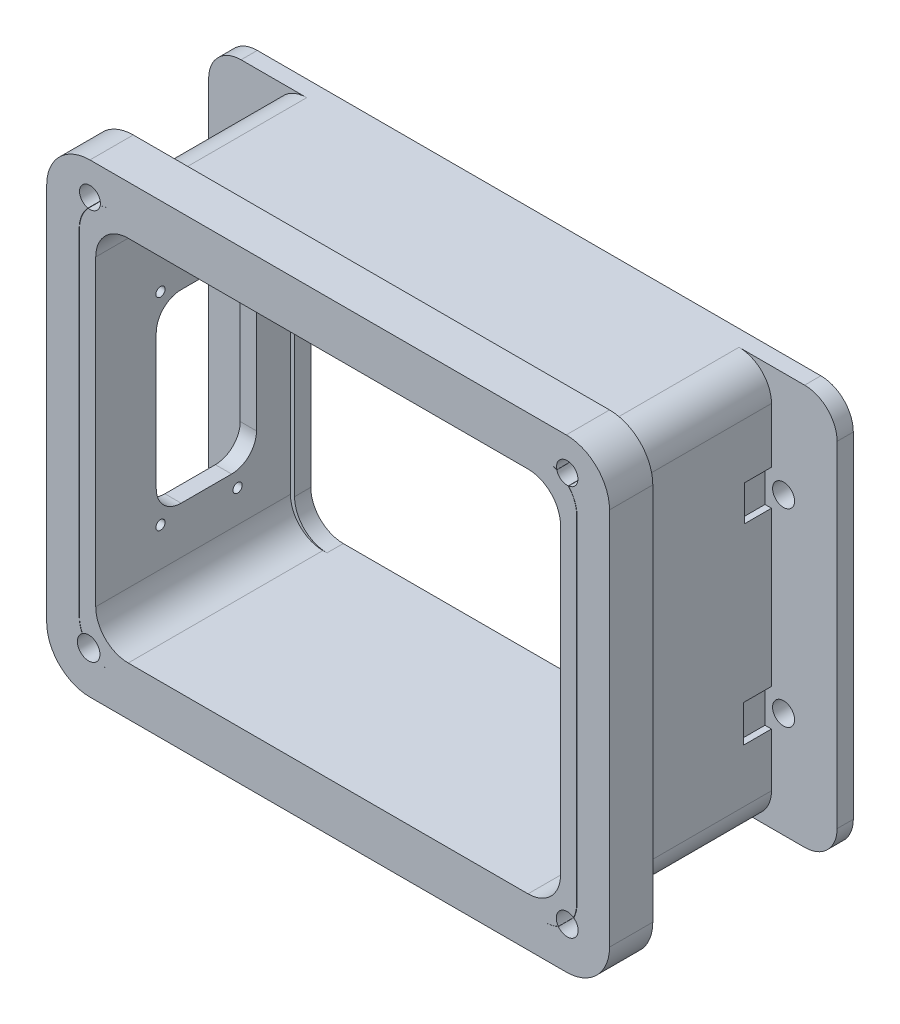
SolidWorks part; units mm, degrees
ref_plane "Front Plane" through (0, 0, 0) normal (0, 0, 1) x (1, 0, 0)
ref_plane "Top Plane" through (0, 0, 0) normal (0, 1, 0) x (1, 0, 0)
ref_plane "Right Plane" through (0, 0, 0) normal (1, 0, 0) x (0, 0, -1)
sketch "Sketch1" plane through (0, 0, 0) normal (0, 0, 1) x (1, 0, 0)
  line L0 (66.1502, -46.99) -> (-66.1502, -46.99)
  line L1 (73.7702, -39.37) -> (73.7702, 39.37)
  line L2 (66.1502, 46.99) -> (-66.1502, 46.99)
  line L3 (-73.7702, -39.37) -> (-73.7702, 39.37)
  line L4 (73.7702, -46.99) -> (-73.7702, 46.99) construction
  line L5 (73.7702, 46.99) -> (-73.7702, -46.99) construction
  line L6 (45.9749, -43.18) -> (-45.9749, -43.18)
  line L7 (53.5949, -35.56) -> (53.5949, 35.56)
  line L8 (45.9749, 43.18) -> (-45.9749, 43.18)
  line L9 (-53.5949, -35.56) -> (-53.5949, 35.56)
  line L10 (53.5949, -43.18) -> (-53.5949, 43.18) construction
  line L11 (53.5949, 43.18) -> (-53.5949, -43.18) construction
  arc A0 (-66.1502, 46.99) -> (-73.7702, 39.37) centre (-66.1502, 39.37) ccw
  arc A1 (73.7702, 39.37) -> (66.1502, 46.99) centre (66.1502, 39.37) ccw
  arc A2 (66.1502, -46.99) -> (73.7702, -39.37) centre (66.1502, -39.37) ccw
  arc A3 (-66.1502, -46.99) -> (-73.7702, -39.37) centre (-66.1502, -39.37) cw
  arc A4 (-45.9749, 43.18) -> (-53.5949, 35.56) centre (-45.9749, 35.56) ccw
  arc A5 (-45.9749, -43.18) -> (-53.5949, -35.56) centre (-45.9749, -35.56) cw
  arc A6 (45.9749, -43.18) -> (53.5949, -35.56) centre (45.9749, -35.56) ccw
  arc A7 (53.5949, 35.56) -> (45.9749, 43.18) centre (45.9749, 35.56) ccw
  point P0 (0, 0)
  point P5 (0, 0)
  dimension "D1" = 7.62
  dimension "D2" = 7.62
  dimension "D3" = 7.62
  dimension "D4" = 7.62
  dimension "D5" = 7.62
  dimension "D6" = 7.62
  dimension "D7" = 7.62
  dimension "D8" = 7.62
  dimension "D9" = 3.81
  dimension "D10" = 93.98
extrude "Boss-Extrude1" add sketch "Sketch1" along normal blind 3.81
sketch "Sketch2" plane through (0, 0, 3.81) normal (0, 0, 1) x (1, 0, 0)
  line L0 (66.1502, 46.99) -> (-66.1502, 46.99) construction
  line L1 (46.9359, -43.18) -> (-46.9359, -43.18)
  line L2 (54.5559, -35.56) -> (54.5559, 35.56)
  line L3 (46.9359, 43.18) -> (-46.9359, 43.18)
  line L4 (-54.5559, -35.56) -> (-54.5559, 35.56)
  line L5 (54.5559, -43.18) -> (-54.5559, 43.18) construction
  line L6 (54.5559, 43.18) -> (-54.5559, -43.18) construction
  line L7 (50.7459, -46.99) -> (-50.7459, -46.99)
  line L8 (58.3659, -39.37) -> (58.3659, 39.37)
  line L9 (50.7459, 46.99) -> (-50.7459, 46.99)
  line L10 (-58.3659, -39.37) -> (-58.3659, 39.37)
  line L11 (58.3659, -46.99) -> (-58.3659, 46.99) construction
  line L12 (58.3659, 46.99) -> (-58.3659, -46.99) construction
  arc A0 (-46.9359, 43.18) -> (-54.5559, 35.56) centre (-46.9359, 35.56) ccw
  arc A1 (54.5559, 35.56) -> (46.9359, 43.18) centre (46.9359, 35.56) ccw
  arc A2 (46.9359, -43.18) -> (54.5559, -35.56) centre (46.9359, -35.56) ccw
  arc A3 (-46.9359, -43.18) -> (-54.5559, -35.56) centre (-46.9359, -35.56) cw
  arc A4 (-50.7459, 46.99) -> (-58.3659, 39.37) centre (-50.7459, 39.37) ccw
  arc A5 (58.3659, 39.37) -> (50.7459, 46.99) centre (50.7459, 39.37) ccw
  arc A6 (50.7459, -46.99) -> (58.3659, -39.37) centre (50.7459, -39.37) ccw
  arc A7 (-50.7459, -46.99) -> (-58.3659, -39.37) centre (-50.7459, -39.37) cw
  point P0 (0, 0)
  point P18 (0, 0)
  dimension "D3" = 7.62
  dimension "D4" = 7.62
  dimension "D5" = 7.62
  dimension "D6" = 7.62
  dimension "D9" = 7.62
  dimension "D10" = 7.62
  dimension "D11" = 7.62
  dimension "D12" = 7.62
  dimension "D2" = 3.81
  dimension "D7" = 3.81
  dimension "D8" = 116.7317
extrude "Boss-Extrude2" add sketch "Sketch2" along normal blind 45.72
sketch "Sketch4" plane through (0, 0, 3.81) normal (0, 0, 1) x (1, 0, 0)
  circle A0 centre (61.206, 22.2292) radius 2.58
  circle A1 centre (61.206, -22.2208) radius 2.58
  circle A2 centre (-60.974, -22.2208) radius 2.58
  circle A3 centre (-60.974, 22.2292) radius 2.58
extrude "Cut-Extrude1" cut sketch "Sketch4" against normal up to next
sketch "Sketch7" plane through (-58.3659, 0, 0) normal (-1, 0, 0) x (0, 0, 1)
  line L0 (11.7913, 13.0336) -> (11.7913, -18.6824)
  line L1 (17.6333, 18.8756) -> (29.482, 18.8756)
  line L2 (35.324, 13.0336) -> (35.324, -18.6824)
  line L3 (17.6333, -24.5244) -> (29.482, -24.5244)
  arc A0 (11.7913, 13.0336) -> (17.6333, 18.8756) centre (17.6333, 13.0336) cw
  arc A1 (29.482, 18.8756) -> (35.324, 13.0336) centre (29.482, 13.0336) cw
  arc A2 (35.324, -18.6824) -> (29.482, -24.5244) centre (29.482, -18.6824) cw
  arc A3 (11.7913, -18.6824) -> (17.6333, -24.5244) centre (17.6333, -18.6824) ccw
  dimension "D1" = 5.842
  dimension "D2" = 5.842
  dimension "D3" = 5.842
  dimension "D4" = 5.842
extrude "Cut-Extrude2" cut sketch "Sketch7" against normal up to next
sketch "Sketch8" plane through (-54.5559, 0, 0) normal (1, 0, 0) x (0, 0, -1)
  circle A0 centre (-34.324, -26.5244) radius 1.085
  circle A1 centre (-16.224, -28.0244) radius 1.085
  circle A2 centre (-16.224, 22.3756) radius 1.085
  circle A3 centre (-34.324, 20.8756) radius 1.085
extrude "Cut-Extrude3" cut sketch "Sketch8" against normal up to next
ref_plane "Plane2" through (53.5949, 35.56, 0) normal (0, 1, 0) x (1, 0, 0)
sketch "Sketch10" plane through (-58.3659, 0, 0) normal (-1, 0, 0) x (0, 0, 1)
  line L0 (3.81, 39.37) -> (3.81, -39.37) construction
  line L1 (3.81, 26.4109) -> (10.0914, 26.4109)
  line L2 (3.81, 26.4109) -> (3.81, 18.0723)
  line L3 (3.81, 18.0723) -> (10.0914, 18.0723)
  line L4 (10.0914, 26.4109) -> (10.0914, 18.0723)
  line L6 (3.81, -18.1506) -> (10.4218, -18.1506)
  line L7 (3.81, -18.1506) -> (3.81, -26.8135)
  line L8 (3.81, -26.8135) -> (10.4218, -26.8135)
  line L9 (10.4218, -18.1506) -> (10.4218, -26.8135)
extrude "Cut-Extrude4" cut sketch "Sketch10" against normal blind 1.524
ref_plane "Plane3" through (0, 0, 0) normal (-1, 0, 0) x (0, 0, 1)
mirror "Mirror1" about plane through (0, 0, 0) normal (-1, 0, 0) of "Cut-Extrude4"
sketch "Sketch11" plane through (0, 0, 49.53) normal (0, 0, 1) x (1, 0, 0)
  line L0 (-50.7459, 46.99) -> (-66.1502, 46.99) construction
  line L1 (50.828, -46.99) -> (-50.828, -46.99)
  line L2 (58.448, -39.37) -> (58.448, 39.37)
  line L3 (50.828, 46.99) -> (-50.828, 46.99)
  line L4 (-58.448, -39.37) -> (-58.448, 39.37)
  line L5 (58.448, -46.99) -> (-58.448, 46.99) construction
  line L6 (58.448, 46.99) -> (-58.448, -46.99) construction
  line L8 (55.908, -54.61) -> (-55.908, -54.61)
  line L9 (66.068, -44.45) -> (66.068, 44.45)
  line L10 (55.908, 54.61) -> (-55.908, 54.61)
  line L11 (-66.068, -44.45) -> (-66.068, 44.45)
  line L12 (66.068, -54.61) -> (-66.068, 54.61) construction
  line L13 (66.068, 54.61) -> (-66.068, -54.61) construction
  arc A0 (-50.828, 46.99) -> (-58.448, 39.37) centre (-50.828, 39.37) ccw
  arc A1 (58.448, 39.37) -> (50.828, 46.99) centre (50.828, 39.37) ccw
  arc A2 (50.828, -46.99) -> (58.448, -39.37) centre (50.828, -39.37) ccw
  arc A3 (-50.828, -46.99) -> (-58.448, -39.37) centre (-50.828, -39.37) cw
  arc A4 (-55.908, 54.61) -> (-66.068, 44.45) centre (-55.908, 44.45) ccw
  arc A5 (66.068, 44.45) -> (55.908, 54.61) centre (55.908, 44.45) ccw
  arc A6 (55.908, -54.61) -> (66.068, -44.45) centre (55.908, -44.45) ccw
  arc A7 (-55.908, -54.61) -> (-66.068, -44.45) centre (-55.908, -44.45) cw
  point P0 (0, 0)
  point P20 (0, 0)
  dimension "D1" = 7.62
  dimension "D2" = 7.62
  dimension "D3" = 7.62
  dimension "D4" = 7.62
  dimension "D7" = 10.16
  dimension "D8" = 10.16
  dimension "D9" = 10.16
  dimension "D10" = 10.16
  dimension "D5" = 7.62
  dimension "D6" = 7.62
extrude "Boss-Extrude3" add sketch "Sketch11" against normal blind 10.16
sketch "Sketch12" plane through (0, 0, 49.53) normal (0, 0, 1) x (1, 0, 0)
  circle A0 centre (-55.908, 46.99) radius 2.4475
  circle A2 centre (56.134, -44.7582) radius 2.5707
  arc A3 (50.7459, -46.99) -> (58.3659, -39.37) centre (50.7459, -39.37) ccw construction
  circle A4 centre (-56.2162, -44.7582) radius 2.6491
  arc A5 (-58.448, -39.37) -> (-50.828, -46.99) centre (-50.828, -39.37) ccw construction
  circle A6 centre (56.134, 46.99) radius 2.5148
extrude "Cut-Extrude5" cut sketch "Sketch12" against normal blind 5.08
